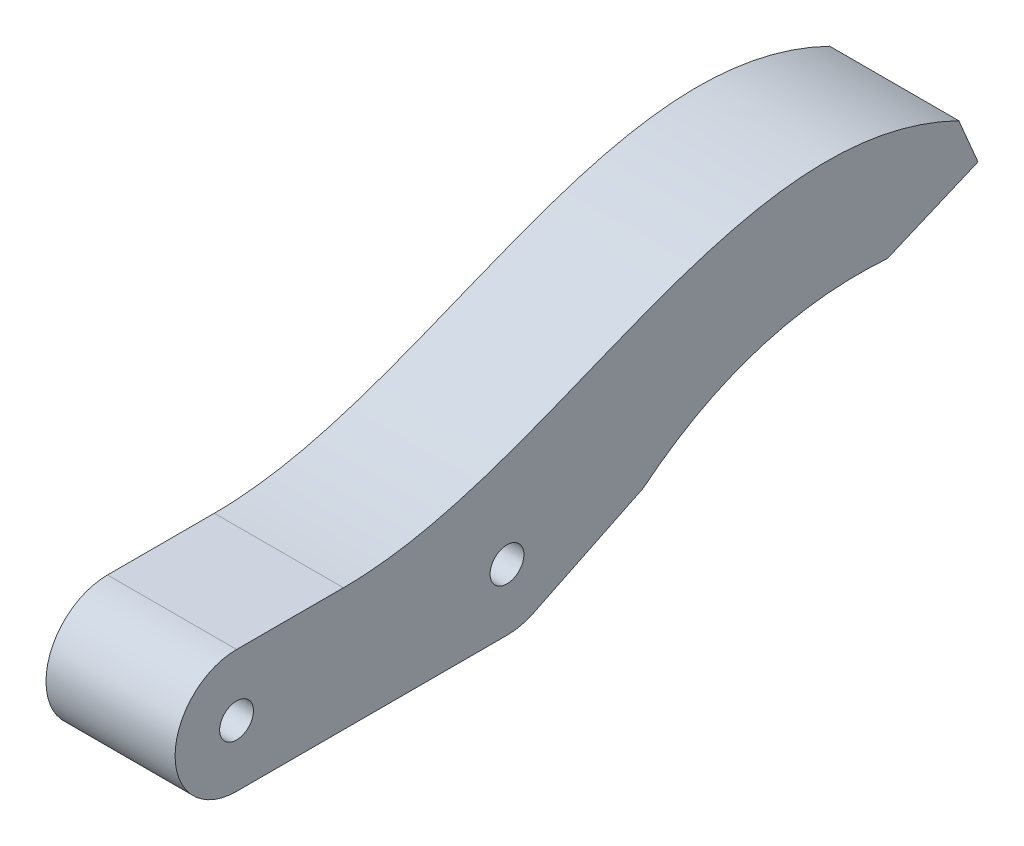
SolidWorks part; units mm, degrees
material "Balsa"
ref_plane "Front Plane" through (0, 0, 0) normal (0, 0, 1) x (1, 0, 0)
ref_plane "Top Plane" through (0, 0, 0) normal (0, 1, 0) x (1, 0, 0)
ref_plane "Right Plane" through (0, 0, 0) normal (1, 0, 0) x (0, 0, -1)
sketch "Sketch1" plane through (0, 0, 0) normal (1, 0, 0) x (0, 0, -1)
  line L1 (0, 0) -> (27, 0)
  line L2 (0, 0) -> (0, 10)
  line L3 (0, 10) -> (27, 10)
  circle A0 centre (5, 5) radius 1.75
  circle A1 centre (5, 5) radius 5
  circle A2 centre (27, 5) radius 5
  circle A3 centre (27, 5) radius 1.75
  dimension "D7" = 3.5
  dimension "D11" = 10
  dimension "D2" = 3.5
  dimension "D1" = 10
  dimension "D8" = 5
  dimension "D9" = 5
  dimension "D10" = 22
extrude "Boss-Extrude1" add sketch "Sketch1" along normal blind 10.5 contours A1 A0 | A2 L3 A1 L1 | A2 A3 | L2 A1 | L1 A1 | A3
sketch "Sketch2" plane through (10.5, 0, 0) normal (1, 0, 0) x (0, 0, -1)
  line L6 (5, 10) -> (27, 10) construction
  line L14 (5, 10) -> (27, 10)
  line L20 (29.1838, 0.5021) -> (38.0854, 4.8241)
  line L21 (57.948, 11.0678) -> (65.3138, 14.1895)
  line L22 (65.3138, 14.1895) -> (63.753, 17.8724)
  arc A3 (27, 0) -> (27, 10) centre (27, 5) ccw construction
  arc A4 (27, 0) -> (27, 10) centre (27, 5) ccw
  spline S0 degree 2 poles (38.0854, 4.8241) (46.7975, 11.8952) (57.948, 11.0678) knots 0 0 0 1 1 1
  spline S1 degree 3 poles (63.753, 17.8724) (45.9289, 26.5638) (31.0593, 10) (13.695, 10) knots 0 0 0 0 1 1 1 1
  point P2 (27, 5)
  dimension "D3" = 4
  dimension "D4" = 8
extrude "Boss-Extrude2" add sketch "Sketch2" against normal up to surface (10.5 mm away) up to face at (0, 5, -16)
sketch "Sketch3" plane through (10.5, 0, 0) normal (1, 0, 0) x (0, 0, -1)
  circle A0 centre (5, 5) radius 1.375
  circle A2 centre (27, 5) radius 1.375
  dimension "D1" = 2.75
  dimension "D2" = 2.75
extrude "Cut-Extrude1" cut sketch "Sketch3" against normal through all contours A2 | A0
